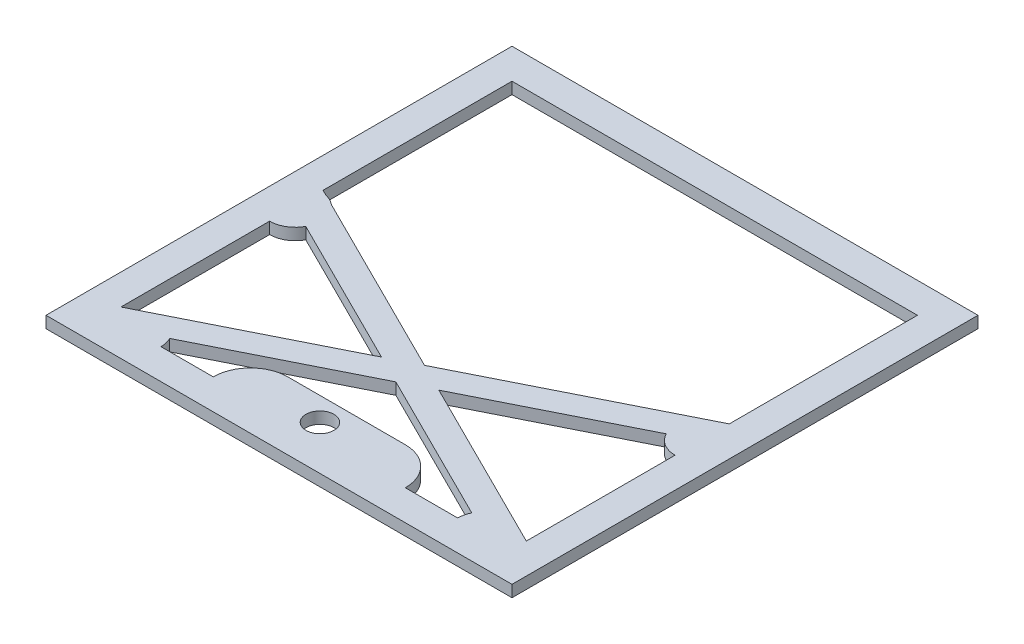
SolidWorks part; units mm, degrees
ref_plane "Front Plane" through (0, 0, 0) normal (0, 0, 1) x (1, 0, 0)
ref_plane "Top Plane" through (0, 0, 0) normal (0, 1, 0) x (1, 0, 0)
ref_plane "Right Plane" through (0, 0, 0) normal (1, 0, 0) x (0, 0, -1)
sketch "Sketch1" plane through (0, 0, 0) normal (0, 1, 0) x (1, 0, 0)
  line L1 (-50, -50) -> (50, -50)
  line L2 (-50, -50) -> (-50, 50)
  line L3 (-50, 50) -> (50, 50)
  line L4 (50, -50) -> (50, 50)
  line L5 (-50, -50) -> (50, 50) construction
  line L6 (-50, 50) -> (50, -50) construction
  line L7 (-43.5, -43.5) -> (43.5, -43.5)
  line L8 (-43.5, -43.5) -> (-43.5, 43.5)
  line L9 (-43.5, 43.5) -> (43.5, 43.5)
  line L10 (43.5, -43.5) -> (43.5, 43.5)
  line L11 (-43.5, -43.5) -> (43.5, 43.5) construction
  line L12 (-43.5, 43.5) -> (43.5, -43.5) construction
  point P0 (0, 0)
  point P6 (0, 0)
  dimension "D1" = 100
  dimension "D2" = 6.5
extrude "Boss-Extrude1" add sketch "Sketch1" along normal blind 2.5
sketch "Sketch2" plane through (0, 2.5, 0) normal (0, 1, 0) x (1, 0, 0)
  line L0 (-12.6151, -43.5) -> (12.6151, -43.5) construction
  line L1 (-43.5, -43.5) -> (43.5, -43.5) construction
  line L2 (-12.6151, -35.5) -> (12.6151, -35.5)
  line L3 (-12.6151, -51.5) -> (12.6151, -51.5)
  arc A0 (-12.6151, -35.5) -> (-12.6151, -51.5) centre (-12.6151, -43.5) ccw
  arc A1 (12.6151, -51.5) -> (12.6151, -35.5) centre (12.6151, -43.5) ccw
  point P4 (0, -43.5)
  dimension "D1" = 8
extrude "Boss-Extrude2" add sketch "Sketch2" against normal blind 2.5
sketch "Sketch3" plane through (0, 2.5, 0) normal (0, 1, 0) x (1, 0, 0)
  line L0 (-50, -50) -> (-17.2788, -50) construction
  line L1 (-27.0449, -50) -> (25.2399, -50)
  line L2 (-27.0449, -50) -> (-27.0449, -57.1355)
  line L3 (-27.0449, -57.1355) -> (25.2399, -57.1355)
  line L4 (25.2399, -50) -> (25.2399, -57.1355)
extrude "Cut-Extrude1" cut sketch "Sketch3" against normal blind 2.5
sketch "Sketch4" plane through (0, 2.5, 0) normal (0, 1, 0) x (1, 0, 0)
  line L0 (-50, -50) -> (50, -50) construction
  line L1 (63.4422, 0) -> (-62.6459, 0) construction
  circle A0 centre (-0.7109, -40.5) radius 3
  dimension "D1" = 6
  dimension "D2" = 9.5
extrude "Cut-Extrude2" cut sketch "Sketch4" against normal blind 2.5 contours A0
sketch "Sketch5" plane through (0, 2.5, 0) normal (0, 1, 0) x (1, 0, 0)
  line L0 (-43.5, -43.5) -> (47, 1.8092)
  line L1 (43.5, -43.5) -> (-47.3614, 1.8092)
extrude "Extrude-Thin2" add sketch "Sketch5" against normal blind 2.5 thin thin type mid plane wall 5.5
sketch "Sketch6" plane through (0, 2.5, 0) normal (0, 1, 0) x (1, 0, 0)
  line L0 (0, 4.6744) -> (0, -57.5759) construction
  circle A0 centre (37.3376, -43.5) radius 5.5
  circle A1 centre (43.5, -3.0185) radius 5.5
  circle A2 centre (-37.3376, -43.5) radius 5.5
  circle A3 centre (-43.5, -3.0185) radius 5.5
extrude "Boss-Extrude3" add sketch "Sketch6" against normal blind 2.5
